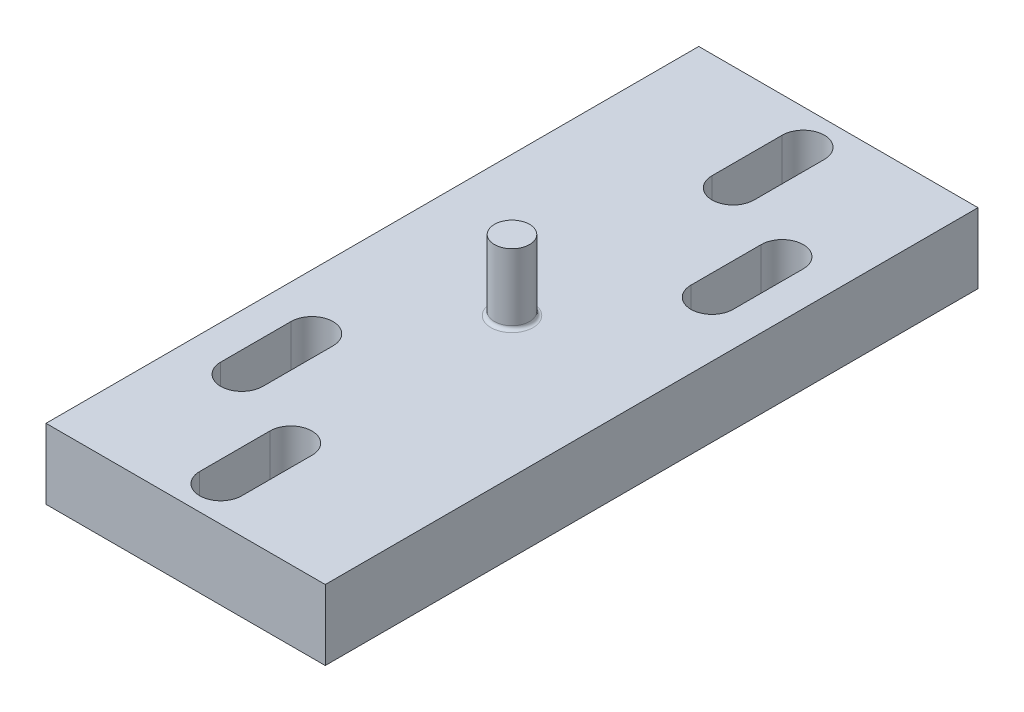
SolidWorks part; units mm, degrees
ref_plane "Front Plane" through (0, 0, 0) normal (0, 0, 1) x (1, 0, 0)
ref_plane "Top Plane" through (0, 0, 0) normal (0, 1, 0) x (1, 0, 0)
ref_plane "Right Plane" through (0, 0, 0) normal (1, 0, 0) x (0, 0, -1)
sketch "10" plane through (0, 0, 0) normal (0, 1, 0) x (1, 0, 0)
  line L0 (-15, 31.5) -> (15, 31.5) construction
  line L1 (-14.8938, 29.7182) -> (14.8938, 33.2818)
  line L2 (-14.8938, 29.7182) -> (-12, 15)
  line L3 (14.8938, 33.2818) -> (12, 48)
  line L4 (-12, 15) -> (0, 15)
  line L5 (12, 48) -> (0, 48)
  line L6 (0, 48) -> (0, 63)
  line L7 (0, 15) -> (0, 0)
  point P4 (0, 31.5)
  point P5 (0, 31.5)
  dimension "D1" = 15
  dimension "D2" = 12
  dimension "D3" = 15
  dimension "D4" = 30
  dimension "D5" = 30
  dimension "D6" = 15
  dimension "D7" = 0
  dimension "D8" = 0
  dimension "D9" = 31.5
sketch "01" plane through (0, 0, 0) normal (0, 1, 0) x (1, 0, 0)
  line L0 (-15, 31.5) -> (15, 31.5) construction
  line L1 (-9.3393, 19.7621) -> (9.3393, 43.2379)
  line L2 (-9.3393, 19.7621) -> (-12, 5)
  line L3 (9.3393, 43.2379) -> (12, 58)
  line L4 (-12, 5) -> (0, 5)
  line L5 (12, 58) -> (0, 58)
  line L6 (0, 58) -> (0, 73)
  line L7 (0, 5) -> (0, -10)
  point P4 (0, 31.5)
  point P5 (0, 31.5)
  dimension "D1" = 30
  dimension "D2" = 15
  dimension "D3" = 12
  dimension "D4" = 15
  dimension "D5" = 30
  dimension "D6" = 0
  dimension "D7" = 41.5
  dimension "D8" = 0
  dimension "D9" = 15
sketch "Sketch2" plane through (0, 0, 0) normal (0, 1, 0) x (1, 0, 0)
  line L1 (-19.8938, 78) -> (0, 78)
  line L2 (-19.8938, 78) -> (-19.8938, -15)
  line L3 (-19.8938, -15) -> (0, -15)
  line L9 (-15, 31.5) -> (15, 31.5) construction
  line L12 (0, 78) -> (0, 76)
  line L14 (-3, 0) -> (-3, -10)
  line L16 (0, -15) -> (0, -13)
  line L19 (-3, 73) -> (-3, 63)
  line L21 (0, 60) -> (0, 3)
  circle A7 centre (-14.8938, 29.7182) radius 5 construction
  arc A12 (-3, -10) -> (0, -13) centre (0, -10) ccw
  arc A13 (0, 3) -> (-3, 0) centre (0, 0) ccw
  arc A17 (0, 76) -> (-3, 73) centre (0, 73) ccw
  arc A18 (-3, 63) -> (0, 60) centre (0, 63) ccw
  dimension "D2" = 6
  dimension "D3" = 6
  dimension "D4" = 6
  dimension "D5" = 6
  dimension "D8" = 10
  dimension "D7" = 10
  dimension "D6" = 10
  dimension "D9" = 2
  dimension "D10" = 19.8938
  dimension "D11" = 5
  dimension "D12" = 2
  dimension "D13" = 19.8938
  dimension "D14" = 57
extrude "Boss-Extrude1" add sketch "Sketch2" along normal blind 10 contours L2 L3 L16 A12 L14 A13 L21 A18 L19 A17 L12 L1
mirror "Mirror1" of "Boss-Extrude1"
sketch "Sketch4" plane through (0, 0, 0) normal (0, 1, 0) x (1, 0, 0)
  line L4 (-15, 31.5) -> (15, 31.5) construction
  line L5 (-15, 31.5) -> (15, 31.5) construction
  line L7 (0, 78) -> (0, -15) construction
  line L12 (-19.8938, -15) -> (19.8938, -15) construction
  line L13 (-19.8938, 78) -> (19.8938, 78) construction
  line L14 (-15, 15) -> (-15, 5)
  line L15 (-9, 15) -> (-9, 5)
  line L16 (15, 15) -> (15, 5) construction
  line L17 (9, 15) -> (9, 5) construction
  line L18 (15, 48) -> (15, 58)
  line L19 (9, 48) -> (9, 58)
  arc A8 (-15, 5) -> (-9, 5) centre (-12, 5) ccw
  arc A9 (-9, 15) -> (-15, 15) centre (-12, 15) ccw
  arc A10 (9, 15) -> (15, 15) centre (12, 15) cw construction
  arc A11 (15, 5) -> (9, 5) centre (12, 5) cw construction
  arc A12 (15, 58) -> (9, 58) centre (12, 58) ccw
  arc A13 (9, 48) -> (15, 48) centre (12, 48) ccw
  dimension "D1" = 6
  dimension "D2" = 6
  dimension "D3" = 10
  dimension "D4" = 10
extrude "Cut-Extrude1" cut sketch "Sketch4" along normal through all
sketch "Sketch5" plane through (0, 10, 0) normal (0, 1, 0) x (1, 0, 0)
  line L0 (-14.8938, 29.7182) -> (14.8938, 33.2818) construction
  circle A0 centre (0, 31.5) radius 2.5
  dimension "D1" = 5
extrude "Boss-Extrude2" add sketch "Sketch5" along normal blind 10
fillet "Fillet1" radius 0.5 1 edges at (0, 10, -29)
